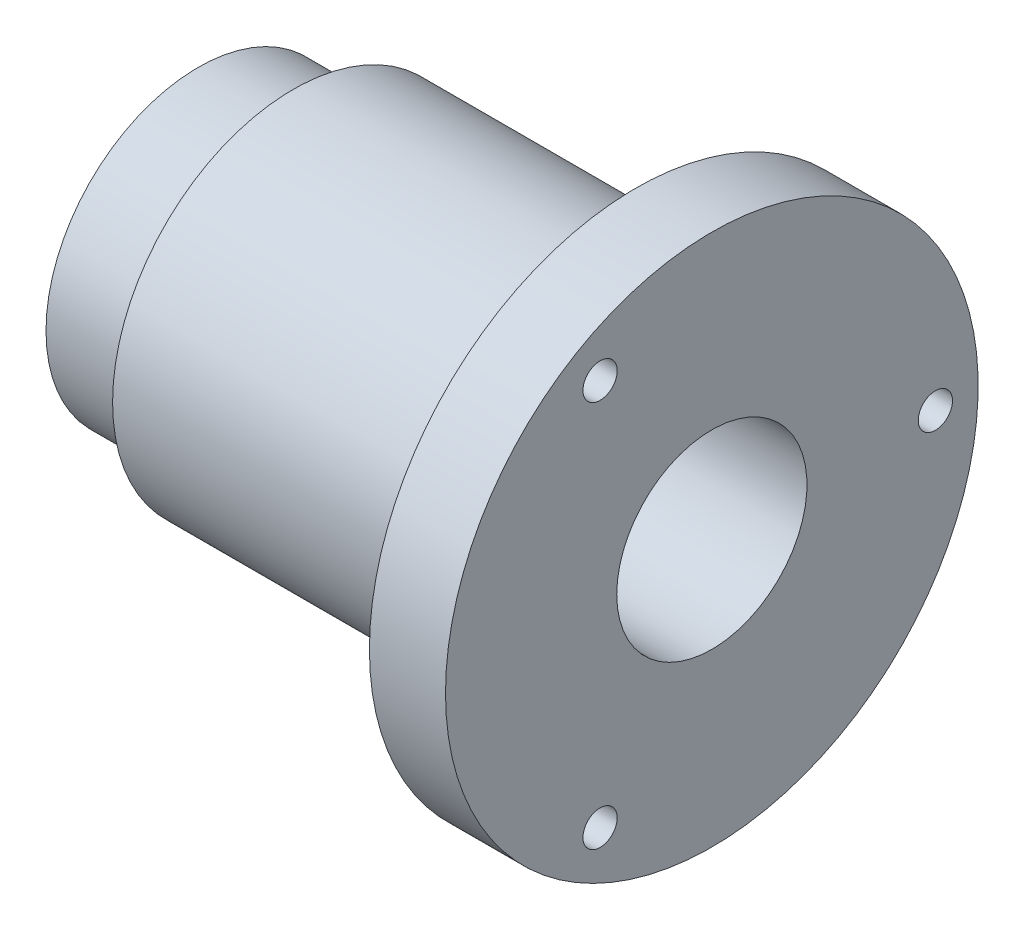
SolidWorks part; units mm, degrees
ref_plane "Front Plane" through (0, 0, 0) normal (0, 0, 1) x (1, 0, 0)
ref_plane "Top Plane" through (0, 0, 0) normal (0, 1, 0) x (1, 0, 0)
ref_plane "Right Plane" through (0, 0, 0) normal (1, 0, 0) x (0, 0, -1)
sketch "Sketch1" plane through (0, 0, 0) normal (0, 1, 0) x (1, 0, 0)
  line L0 (0, 0) -> (23.1328, 0) construction
  line L1 (0, 5) -> (27, 5)
  line L2 (0, 5) -> (0, 8)
  line L3 (0, 8) -> (5, 8)
  line L4 (5, 8) -> (5, 9.5)
  line L5 (5, 9.5) -> (23, 9.5)
  line L6 (23, 9.5) -> (23, 14)
  line L7 (23, 14) -> (27, 14)
  line L8 (27, 14) -> (27, 5)
  dimension "D1" = 10
  dimension "D2" = 19
  dimension "D3" = 3
  dimension "D4" = 5
  dimension "D5" = 18
  dimension "D6" = 28
  dimension "D7" = 4
revolve "Revolve1" add sketch "Sketch1" angle 360 about L0
sketch "Sketch2" plane through (23, 0, 0) normal (-1, 0, 0) x (0, 0, 1)
  line L1 (-9.5, 0) -> (-14, 0) construction
  circle A0 centre (0, 0) radius 9.5 construction
  circle A1 centre (0, 0) radius 14 construction
  circle A2 centre (-11.75, 0) radius 0.9
  dimension "D1" = 1.8
extrude "Cut-Extrude1" cut sketch "Sketch2" against normal through all
pattern_circular "CirPattern1" count 3 over 360 about axis through (0, 0, 0) along (1, 0, 0) of "Cut-Extrude1"
